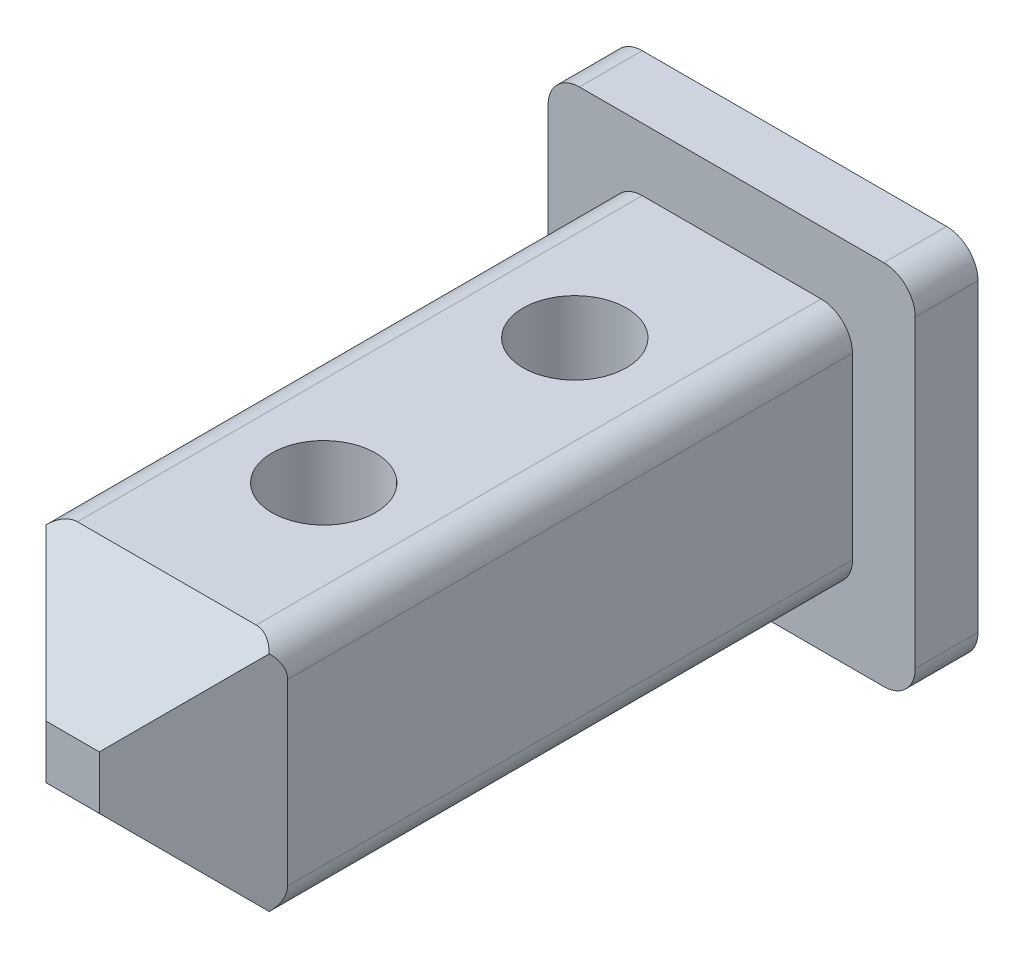
SolidWorks part; units mm, degrees
material "ABS"
ref_plane "前视基准面" through (0, 0, 0) normal (0, 0, 1) x (1, 0, 0)
ref_plane "上视基准面" through (0, 0, 0) normal (0, 1, 0) x (1, 0, 0)
ref_plane "右视基准面" through (0, 0, 0) normal (1, 0, 0) x (0, 0, -1)
sketch "草图1" plane through (0, 0, 0) normal (0, 0, 1) x (1, 0, 0)
  line L5 (-3.85, 3.85) -> (3.85, 3.85)
  line L6 (-3.85, 3.85) -> (-3.85, -3.85)
  line L7 (-3.85, -3.85) -> (3.85, -3.85)
  line L8 (3.85, 3.85) -> (3.85, -3.85)
  line L9 (-3.85, 3.85) -> (3.85, -3.85) construction
  line L10 (-3.85, -3.85) -> (3.85, 3.85) construction
  point P0 (0, 0)
  dimension "D1" = 7.7
extrude "凸台-拉伸1" add sketch "草图1" along normal blind 21
sketch "草图2" plane through (0, 0, 0) normal (0, 0, -1) x (-1, 0, 0)
  line L1 (-5.85, 5.85) -> (5.85, 5.85)
  line L2 (-5.85, 5.85) -> (-5.85, -5.85)
  line L3 (-5.85, -5.85) -> (5.85, -5.85)
  line L4 (5.85, 5.85) -> (5.85, -5.85)
  line L5 (-5.85, 5.85) -> (5.85, -5.85) construction
  line L6 (-5.85, -5.85) -> (5.85, 5.85) construction
  point P0 (0, 0)
  dimension "D1" = 11.7
extrude "凸台-拉伸2" add sketch "草图2" along normal blind 2
ref_plane "基准面1" through (0, 0, 23) normal (0, 0, 1) x (1, 0, 0)
chamfer "倒角1" distance 3 angle 45 4 edges at (-3.85, 0, 21) (0, -3.85, 21) (3.85, 0, 21) (0, 3.85, 21)
fillet "圆角2" radius 1 8 edges at (-5.85, 5.85, -1) (5.85, 5.85, -1) (-5.85, -5.85, -1) (5.85, -5.85, -1) (-3.85, 3.85, 9) (-3.85, -3.85, 9) (3.85, -3.85, 9) (3.85, 3.85, 9)
sketch "草图5" plane through (0, -3.85, 0) normal (0, -1, 0) x (1, 0, 0)
  line L0 (4.85, 0) -> (-4.85, 0) construction
  circle A0 centre (0, 5) radius 1.65
  circle A1 centre (0, 13) radius 1.65
  dimension "D1" = 3.3
  dimension "D2" = 5
  dimension "D3" = 3.3
  dimension "D4" = 8
extrude "切除-拉伸2" cut sketch "草图5" against normal blind 24
